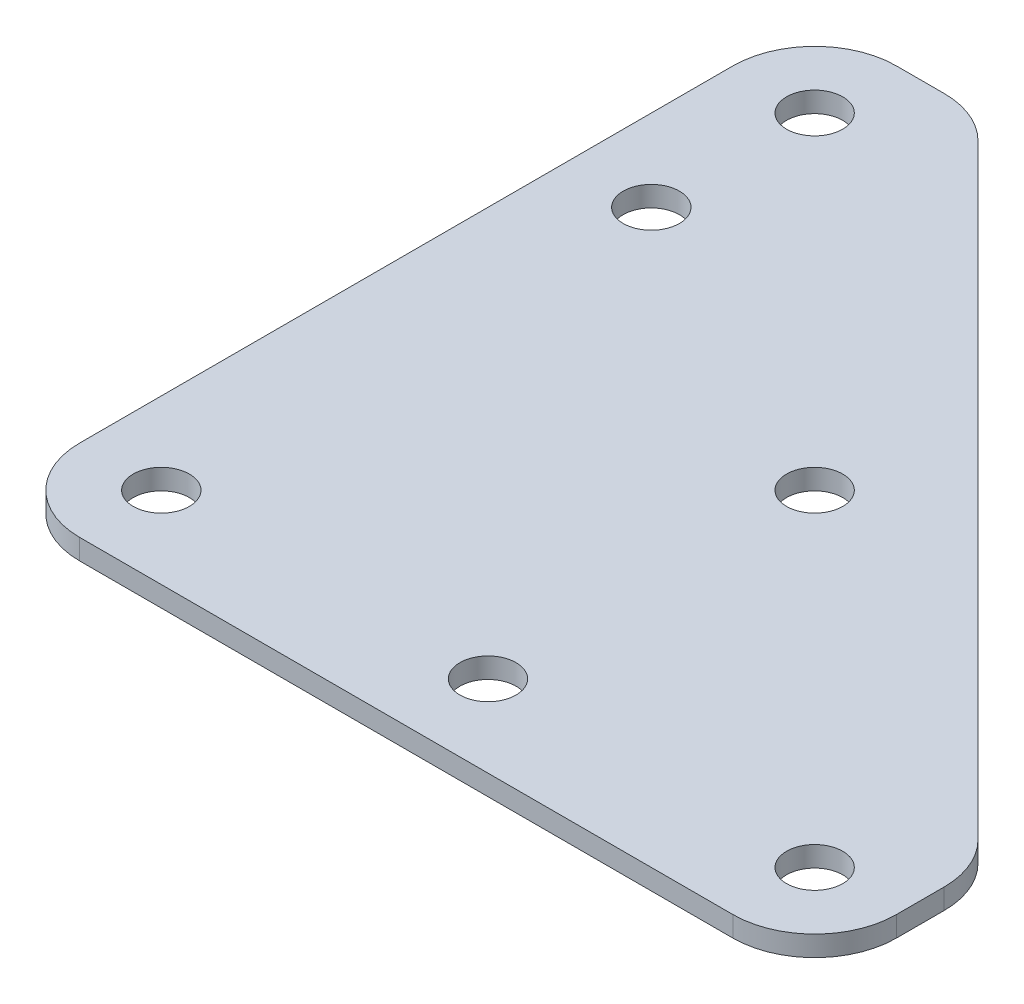
SolidWorks part; units mm, degrees
ref_plane "Front Plane" through (0, 0, 0) normal (0, 0, 1) x (1, 0, 0)
ref_plane "Top Plane" through (0, 0, 0) normal (0, 1, 0) x (1, 0, 0)
ref_plane "Right Plane" through (0, 0, 0) normal (1, 0, 0) x (0, 0, -1)
sketch "Sketch1" plane through (0, 0, 0) normal (0, 1, 0) x (1, 0, 0)
  line L0 (-6.35, 0) -> (-6.35, 50.8)
  line L1 (0, 57.15) -> (3.7197, 57.15)
  line L2 (8.2099, 55.2901) -> (55.2901, 8.2099)
  line L3 (57.15, 3.7197) -> (57.15, 0)
  line L4 (50.8, -6.35) -> (0, -6.35)
  circle A0 centre (0, 0) radius 2.1828
  circle A1 centre (0, 50.8) radius 2.1828
  circle A2 centre (50.8, 0) radius 2.1828
  circle A3 centre (25.4, 0) radius 2.1828
  circle A4 centre (0, 38.1) radius 2.1828
  arc A5 (57.15, 0) -> (50.8, -6.35) centre (50.8, 0) cw
  arc A6 (55.2901, 8.2099) -> (57.15, 3.7197) centre (50.8, 3.7197) cw
  arc A7 (3.7197, 57.15) -> (8.2099, 55.2901) centre (3.7197, 50.8) cw
  arc A8 (-6.35, 50.8) -> (0, 57.15) centre (0, 50.8) cw
  arc A9 (-6.35, 0) -> (0, -6.35) centre (0, 0) ccw
  circle A10 centre (25.4, 25.4) radius 2.1828
  point P18 (57.15, -6.35)
  point P21 (57.15, 6.35)
  point P24 (6.35, 57.15)
  point P27 (-6.35, 57.15)
  point P32 (0, 0)
  point P33 (0, 0)
  dimension "D3" = 4.3656
  dimension "D4" = 4.3656
  dimension "D5" = 4.3656
  dimension "D8" = 4.3656
  dimension "D9" = 4.3656
  dimension "D16" = 6.35
  dimension "D17" = 4.3656
  dimension "D1" = 50.8
  dimension "D2" = 50.8
  dimension "D6" = 25.4
  dimension "D7" = 38.1
  dimension "D10" = 6.35
  dimension "D11" = 6.35
  dimension "D12" = 6.35
  dimension "D13" = 6.35
  dimension "D14" = 12.7
  dimension "D15" = 12.7
  dimension "D18" = 25.4
extrude "Boss-Extrude1" add sketch "Sketch1" along normal mid plane 1.5875
